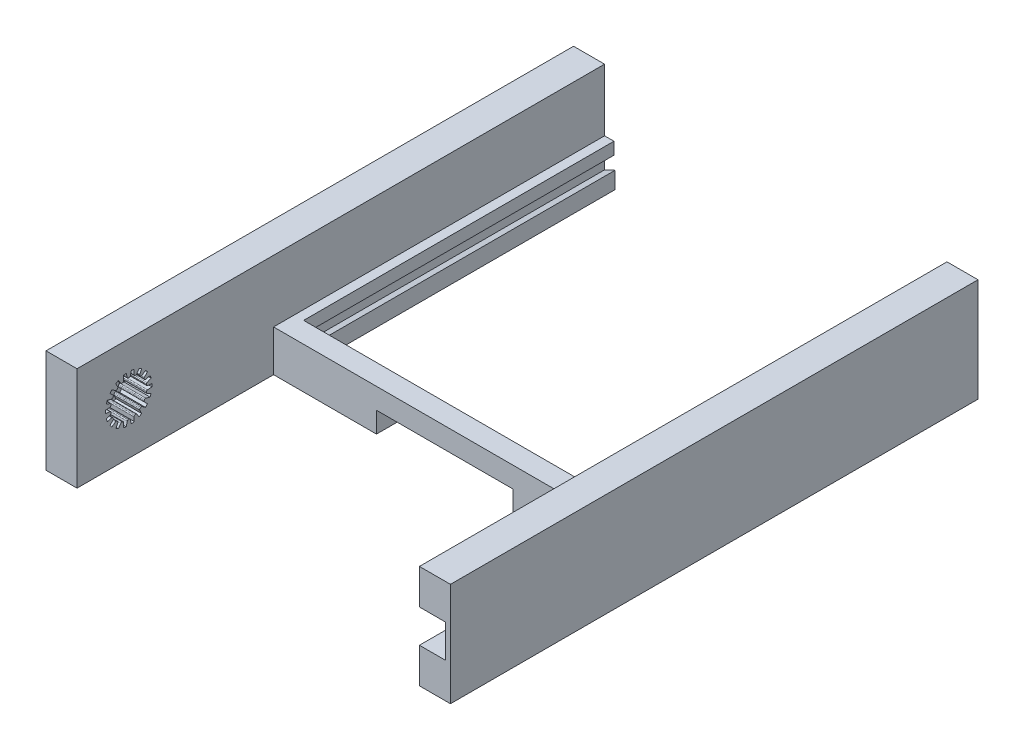
SolidWorks part; units mm, degrees
ref_plane "Front Plane" through (0, 0, 0) normal (0, 0, 1) x (1, 0, 0)
ref_plane "Top Plane" through (0, 0, 0) normal (0, 1, 0) x (1, 0, 0)
ref_plane "Right Plane" through (0, 0, 0) normal (1, 0, 0) x (0, 0, -1)
sketch "Sketch1" plane through (0, 0, 0) normal (0, 1, 0) x (1, 0, 0)
  line L0 (0, -55) -> (0, 55) construction
  line L5 (-19.55, 51) -> (-16.55, 51)
  line L6 (-19.55, 51) -> (-19.55, 0)
  line L7 (-19.55, 0) -> (-16.55, 0)
  line L8 (-16.55, 51) -> (-16.55, 0)
  line L9 (16.55, 51) -> (16.55, 0)
  line L10 (19.55, 0) -> (16.55, 0)
  line L11 (19.55, 51) -> (19.55, 0)
  line L12 (19.55, 51) -> (16.55, 51)
  dimension "D1" = 33.1
  dimension "D2" = 3
  dimension "D3" = 51
extrude "Boss-Extrude1" add sketch "Sketch1" along normal blind 10
sketch "Sketch2" plane through (0, 10, 0) normal (0, 1, 0) x (1, 0, 0)
  line L0 (16.55, 51) -> (16.55, 0) construction
  line L1 (-16.55, 51) -> (16.55, 51)
  line L2 (-16.55, 51) -> (-16.55, 21)
  line L3 (-16.55, 21) -> (16.55, 21)
  line L4 (16.55, 51) -> (16.55, 21)
  dimension "D1" = 30
extrude "Boss-Extrude2" add sketch "Sketch2" along normal blind 4 from surface at -10 starting at face at (18.05, 0, -25.5)
sketch "Sketch3" plane through (0, 10, 0) normal (0, 1, 0) x (1, 0, 0)
  line L0 (-16.55, 51) -> (-19.55, 51) construction
  line L1 (-6.6, 51) -> (6.6, 51)
  line L2 (-6.6, 51) -> (-6.6, 21)
  line L3 (-6.6, 21) -> (6.6, 21)
  line L4 (6.6, 51) -> (6.6, 21)
  line L5 (-16.55, 21) -> (16.55, 21) construction
  point P8 (0, 21)
  dimension "D1" = 13.2
extrude "Cut-Extrude1" cut sketch "Sketch3" along normal blind 2 from surface at -10 starting at face at (0, 0, -18)
sketch "Sketch5" plane through (-19.55, 0, 0) normal (-1, 0, 0) x (0, 0, 1)
  line L36 (-51, 10) -> (0, 10) construction
  line L37 (0, 10) -> (0, 0) construction
  line B0 (-4.75, 7.2361) -> (-4.8548, 6.8247)
  line B1 (-5.1452, 6.8247) -> (-5.25, 7.2361)
  line B2 (-4.5123, 6.7643) -> (-4.4701, 7.1867)
  line B3 (-4.0003, 7.0157) -> (-4.2395, 6.665)
  line B4 (-3.9383, 6.4911) -> (-3.7542, 6.8736)
  line B5 (-3.3712, 6.5522) -> (-3.7159, 6.3045)
  line B6 (-3.4924, 6.0381) -> (-3.1885, 6.3345)
  line B7 (-2.9385, 5.9015) -> (-3.3472, 5.7866)
  line B8 (-3.2283, 5.4598) -> (-2.8413, 5.6345)
  line B9 (-2.7545, 5.1421) -> (-3.1778, 5.1739)
  line B10 (-3.1778, 4.8261) -> (-2.7545, 4.8579)
  line B11 (-2.8413, 4.3655) -> (-3.2283, 4.5402)
  line B12 (-3.3472, 4.2134) -> (-2.9385, 4.0985)
  line B13 (-3.1885, 3.6655) -> (-3.4924, 3.9619)
  line B14 (-3.7159, 3.6955) -> (-3.3712, 3.4478)
  line B15 (-3.7542, 3.1264) -> (-3.9383, 3.5089)
  line B16 (-4.2395, 3.335) -> (-4.0003, 2.9843)
  line B17 (-4.4701, 2.8133) -> (-4.5123, 3.2357)
  line B18 (-4.8548, 3.1753) -> (-4.75, 2.7639)
  line B19 (-5.25, 2.7639) -> (-5.1452, 3.1753)
  line B20 (-5.4877, 3.2357) -> (-5.5299, 2.8133)
  line B21 (-5.9997, 2.9843) -> (-5.7605, 3.335)
  line B22 (-6.0617, 3.5089) -> (-6.2458, 3.1264)
  line B23 (-6.6288, 3.4478) -> (-6.2841, 3.6955)
  line B24 (-6.5076, 3.9619) -> (-6.8115, 3.6655)
  line B25 (-7.0615, 4.0985) -> (-6.6528, 4.2134)
  line B26 (-6.7717, 4.5402) -> (-7.1587, 4.3655)
  line B27 (-7.2455, 4.8579) -> (-6.8222, 4.8261)
  line B28 (-6.8222, 5.1739) -> (-7.2455, 5.1421)
  line B29 (-7.1587, 5.6345) -> (-6.7717, 5.4598)
  line B30 (-6.6528, 5.7866) -> (-7.0615, 5.9015)
  line B31 (-6.8115, 6.3345) -> (-6.5076, 6.0381)
  line B32 (-6.2841, 6.3045) -> (-6.6288, 6.5522)
  line B33 (-6.2458, 6.8736) -> (-6.0617, 6.4911)
  line B34 (-5.7605, 6.665) -> (-5.9997, 7.0157)
  line B35 (-5.5299, 7.1867) -> (-5.4877, 6.7643)
  arc B36 (-5.9997, 7.0157) -> (-6.2458, 6.8736) centre (-5, 5) ccw
  arc B37 (-5.5554, 6.6595) -> (-5.6412, 6.6283) centre (-5, 5) ccw
  arc B38 (-4.9543, 6.7494) -> (-4.8548, 6.8247) centre (-4.9517, 6.8494) ccw
  arc B39 (-5.0457, 6.7494) -> (-5.1452, 6.8247) centre (-5.0483, 6.8494) cw
  arc B40 (-4.4446, 6.6595) -> (-4.5123, 6.7643) centre (-4.4128, 6.7543) cw
  arc B41 (-4.3588, 6.6283) -> (-4.2395, 6.665) centre (-4.3221, 6.7213) ccw
  arc B42 (-3.9105, 6.3695) -> (-3.9383, 6.4911) centre (-3.8482, 6.4477) cw
  arc B43 (-3.8405, 6.3108) -> (-3.7159, 6.3045) centre (-3.7743, 6.3857) ccw
  arc B44 (-3.5078, 5.9142) -> (-3.4924, 6.0381) centre (-3.4225, 5.9665) cw
  arc B45 (-3.4621, 5.8352) -> (-3.3472, 5.7866) centre (-3.3743, 5.8829) ccw
  arc B46 (-3.2851, 5.3487) -> (-3.2283, 5.4598) centre (-3.1871, 5.3687) cw
  arc B47 (-3.2692, 5.2588) -> (-3.1778, 5.1739) centre (-3.1703, 5.2736) ccw
  arc B48 (-3.2692, 4.7412) -> (-3.1778, 4.8261) centre (-3.1703, 4.7264) cw
  arc B49 (-3.2851, 4.6513) -> (-3.2283, 4.5402) centre (-3.1871, 4.6313) ccw
  arc B50 (-3.4621, 4.1648) -> (-3.3472, 4.2134) centre (-3.3743, 4.1171) cw
  arc B51 (-3.5078, 4.0858) -> (-3.4924, 3.9619) centre (-3.4225, 4.0335) ccw
  arc B52 (-3.8405, 3.6892) -> (-3.7159, 3.6955) centre (-3.7743, 3.6143) cw
  arc B53 (-3.9105, 3.6305) -> (-3.9383, 3.5089) centre (-3.8482, 3.5523) ccw
  arc B54 (-4.3588, 3.3717) -> (-4.2395, 3.335) centre (-4.3221, 3.2787) cw
  arc B55 (-4.4446, 3.3405) -> (-4.5123, 3.2357) centre (-4.4128, 3.2457) ccw
  arc B56 (-4.9543, 3.2506) -> (-4.8548, 3.1753) centre (-4.9517, 3.1506) cw
  arc B57 (-5.0457, 3.2506) -> (-5.1452, 3.1753) centre (-5.0483, 3.1506) ccw
  arc B58 (-5.5554, 3.3405) -> (-5.4877, 3.2357) centre (-5.5872, 3.2457) cw
  arc B59 (-5.6412, 3.3717) -> (-5.7605, 3.335) centre (-5.6779, 3.2787) ccw
  arc B60 (-6.0895, 3.6305) -> (-6.0617, 3.5089) centre (-6.1518, 3.5523) cw
  arc B61 (-6.1595, 3.6892) -> (-6.2841, 3.6955) centre (-6.2257, 3.6143) ccw
  arc B62 (-6.4922, 4.0858) -> (-6.5076, 3.9619) centre (-6.5775, 4.0335) cw
  arc B63 (-6.5379, 4.1648) -> (-6.6528, 4.2134) centre (-6.6257, 4.1171) ccw
  arc B64 (-6.7149, 4.6513) -> (-6.7717, 4.5402) centre (-6.8129, 4.6313) cw
  arc B65 (-6.7308, 4.7412) -> (-6.8222, 4.8261) centre (-6.8297, 4.7264) ccw
  arc B66 (-6.7308, 5.2588) -> (-6.8222, 5.1739) centre (-6.8297, 5.2736) cw
  arc B67 (-6.7149, 5.3487) -> (-6.7717, 5.4598) centre (-6.8129, 5.3687) ccw
  arc B68 (-6.5379, 5.8352) -> (-6.6528, 5.7866) centre (-6.6257, 5.8829) cw
  arc B69 (-6.4922, 5.9142) -> (-6.5076, 6.0381) centre (-6.5775, 5.9665) ccw
  arc B70 (-6.1595, 6.3108) -> (-6.2841, 6.3045) centre (-6.2257, 6.3857) cw
  arc B71 (-6.0895, 6.3695) -> (-6.0617, 6.4911) centre (-6.1518, 6.4477) ccw
  arc B72 (-5.6412, 6.6283) -> (-5.7605, 6.665) centre (-5.6779, 6.7213) cw
  arc B73 (-5.5554, 6.6595) -> (-5.4877, 6.7643) centre (-5.5872, 6.7543) ccw
  arc B74 (-4.9543, 6.7494) -> (-5.0457, 6.7494) centre (-5, 5) ccw
  arc B75 (-4.3588, 6.6283) -> (-4.4446, 6.6595) centre (-5, 5) ccw
  arc B76 (-3.8405, 6.3108) -> (-3.9105, 6.3695) centre (-5, 5) ccw
  arc B77 (-3.4621, 5.8352) -> (-3.5078, 5.9142) centre (-5, 5) ccw
  arc B78 (-3.2692, 5.2588) -> (-3.2851, 5.3487) centre (-5, 5) ccw
  arc B79 (-6.0895, 6.3695) -> (-6.1595, 6.3108) centre (-5, 5) ccw
  arc B80 (-6.4922, 5.9142) -> (-6.5379, 5.8352) centre (-5, 5) ccw
  arc B81 (-6.7149, 5.3487) -> (-6.7308, 5.2588) centre (-5, 5) ccw
  arc B82 (-6.7308, 4.7412) -> (-6.7149, 4.6513) centre (-5, 5) ccw
  arc B83 (-6.5379, 4.1648) -> (-6.4922, 4.0858) centre (-5, 5) ccw
  arc B84 (-6.1595, 3.6892) -> (-6.0895, 3.6305) centre (-5, 5) ccw
  arc B85 (-5.6412, 3.3717) -> (-5.5554, 3.3405) centre (-5, 5) ccw
  arc B86 (-5.0457, 3.2506) -> (-4.9543, 3.2506) centre (-5, 5) ccw
  arc B87 (-4.4446, 3.3405) -> (-4.3588, 3.3717) centre (-5, 5) ccw
  arc B88 (-3.9105, 3.6305) -> (-3.8405, 3.6892) centre (-5, 5) ccw
  arc B89 (-3.2851, 4.6513) -> (-3.2692, 4.7412) centre (-5, 5) ccw
  arc B90 (-5.25, 7.2361) -> (-5.5299, 7.1867) centre (-5, 5) ccw
  arc B91 (-4.4701, 7.1867) -> (-4.75, 7.2361) centre (-5, 5) ccw
  arc B92 (-3.7542, 6.8736) -> (-4.0003, 7.0157) centre (-5, 5) ccw
  arc B93 (-3.1885, 6.3345) -> (-3.3712, 6.5522) centre (-5, 5) ccw
  arc B94 (-2.8413, 5.6345) -> (-2.9385, 5.9015) centre (-5, 5) ccw
  arc B95 (-2.7545, 4.8579) -> (-2.7545, 5.1421) centre (-5, 5) ccw
  arc B96 (-2.9385, 4.0985) -> (-2.8413, 4.3655) centre (-5, 5) ccw
  arc B97 (-3.3712, 3.4478) -> (-3.1885, 3.6655) centre (-5, 5) ccw
  arc B98 (-4.0003, 2.9843) -> (-3.7542, 3.1264) centre (-5, 5) ccw
  arc B99 (-4.75, 2.7639) -> (-4.4701, 2.8133) centre (-5, 5) ccw
  arc B100 (-5.5299, 2.8133) -> (-5.25, 2.7639) centre (-5, 5) ccw
  arc B101 (-6.2458, 3.1264) -> (-5.9997, 2.9843) centre (-5, 5) ccw
  arc B102 (-6.8115, 3.6655) -> (-6.6288, 3.4478) centre (-5, 5) ccw
  arc B103 (-7.1587, 4.3655) -> (-7.0615, 4.0985) centre (-5, 5) ccw
  arc B104 (-7.2455, 5.1421) -> (-7.2455, 4.8579) centre (-5, 5) ccw
  arc B105 (-7.0615, 5.9015) -> (-7.1587, 5.6345) centre (-5, 5) ccw
  arc B106 (-6.6288, 6.5522) -> (-6.8115, 6.3345) centre (-5, 5) ccw
  arc B107 (-3.5078, 4.0858) -> (-3.4621, 4.1648) centre (-5, 5) ccw
  dimension "D1" = 5
  dimension "D2" = 5
sketch_block_instance "Block1-1"
sketch_block "Block1" parameters "D1"=0.1, "D2"=0.5
extrude "Cut-Extrude2" cut sketch "Sketch5" along normal blind 2.5 from surface at -3 starting at face at (-16.55, 4.6667, -24)
sketch "Sketch6" plane through (-19.55, 0, 0) normal (-1, 0, 0) x (0, 0, 1)
  line L0 (-51, 10) -> (0, 10) construction
  line L1 (0, 10) -> (0, 0) construction
  circle A0 centre (-5, 5) radius 1.6
  dimension "D3" = 3.2
  dimension "D1" = 5
  dimension "D2" = 5
extrude "Cut-Extrude3" cut sketch "Sketch6" against normal blind 2.5 from surface at -36.1 starting at face at (16.55, 4.6667, -24)
sketch "Sketch9" plane through (0, 10, 0) normal (0, 1, 0) x (1, 0, 0)
  line L1 (16.55, 21) -> (16.55, 0) construction
  line L3 (16.55, 0) -> (19.55, 0) construction
  line L5 (16.55, 5) -> (17.55, 5)
  line L6 (17.55, 5) -> (19.05, 0)
  line L7 (16.55, 5) -> (16.55, 0)
  line L8 (16.55, 0) -> (19.05, 0)
  dimension "D1" = 5
  dimension "D2" = 2.5
  dimension "D3" = 1
extrude "Cut-Extrude4" cut sketch "Sketch9" against normal blind 3.2 from offset 3.4 offset against normal yes
sketch "Sketch10" plane through (0, 0, -51) normal (0, 0, -1) x (-1, 0, 0)
  line L0 (-15.6441, 2.8276) -> (-16.55, 3.25)
  line L1 (-16.55, 3.25) -> (-16.55, 1.15)
  line L2 (-16.55, 1.15) -> (-15.5349, 1.6234)
  line L3 (-19.55, 0) -> (-6.6, 0) construction
  line L9 (-15.5349, -2.2478) -> (-15.5349, 1.6234)
  line L10 (-15.6441, 10.7743) -> (15.6441, 10.7743)
  line L11 (-16.55, 10) -> (-16.55, 4) construction
  line L13 (-15.6441, 10.7743) -> (-15.6441, 2.8276)
  line L14 (0, 55) -> (0, -55) construction
  line L18 (15.5349, -2.2478) -> (15.5349, 1.6234)
  line L19 (16.55, 1.15) -> (15.5349, 1.6234)
  line L20 (16.55, 3.25) -> (16.55, 1.15)
  line L21 (15.6441, 2.8276) -> (16.55, 3.25)
  line L22 (15.6441, 10.7743) -> (15.6441, 2.8276)
  line L23 (15.5349, -2.2478) -> (-15.5349, -2.2478)
  point P2 (-16.55, 2.2)
  dimension "D1" = 2.2
  dimension "D2" = 65
  dimension "D3" = 65
  dimension "D4" = 2.1
extrude "Cut-Extrude6" cut sketch "Sketch10" against normal through all
sketch "Sketch11" plane through (0, 0, 0) normal (0, 1, 0) x (1, 0, 0)
  line L0 (16.55, 51) -> (16.55, 0) construction
  line L1 (-16.55, 21) -> (16.55, 21)
  line L2 (-16.55, 21) -> (-16.55, 19)
  line L3 (-16.55, 19) -> (16.55, 19)
  line L4 (16.55, 21) -> (16.55, 19)
  dimension "D1" = 2
extrude "Boss-Extrude3" add sketch "Sketch11" along normal up to surface (4 mm away) up to face at (16.0971, 4, -36)
sketch "Sketch12" plane through (0, 4, 0) normal (0, 1, 0) x (1, 0, 0)
  line L0 (15.6441, 21) -> (-15.6441, 21) construction
  line L1 (-6.6, 21) -> (6.6, 21)
  line L2 (-6.6, 21) -> (-6.6, 19)
  line L3 (-6.6, 19) -> (6.6, 19)
  line L4 (6.6, 21) -> (6.6, 19)
  line L5 (-16.55, 19) -> (16.55, 19) construction
  point P8 (0, 19)
  dimension "D1" = 13.2
extrude "Cut-Extrude7" cut sketch "Sketch12" along normal blind 2 from surface at -4 starting at face at (0, 0, -23.6667)
